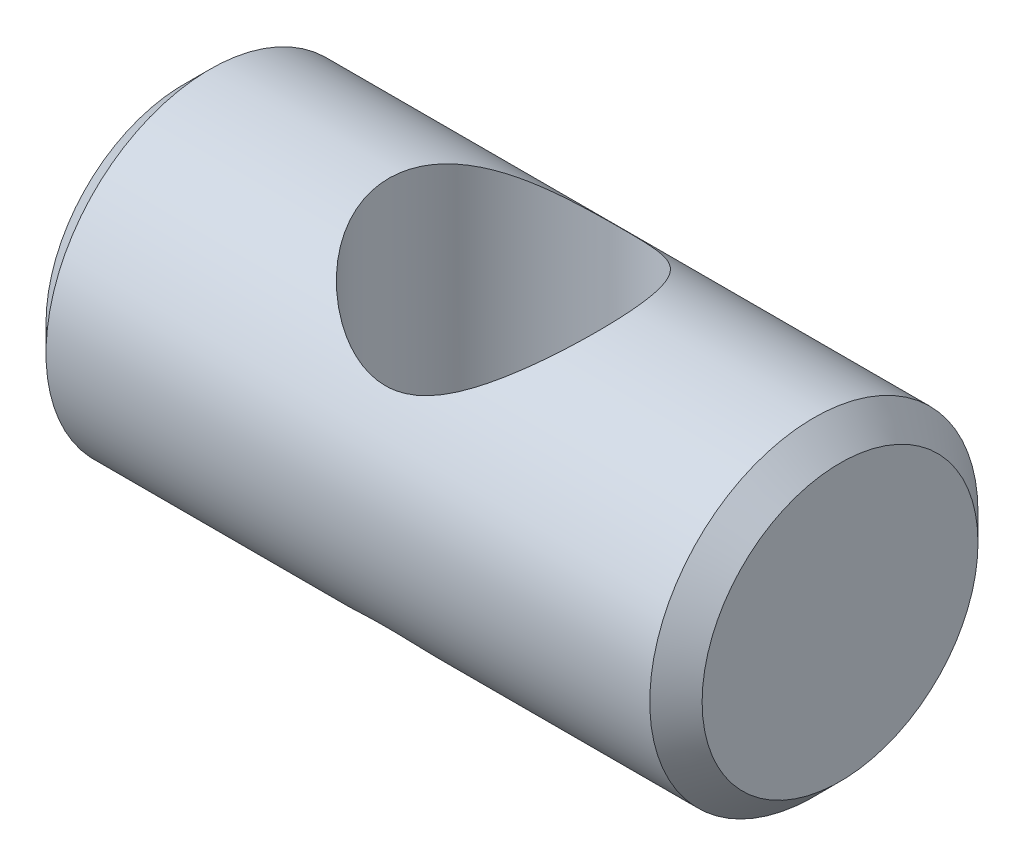
SolidWorks part; units mm, degrees
ref_plane "Front Plane" through (0, 0, 0) normal (0, 0, 1) x (1, 0, 0)
ref_plane "Top Plane" through (0, 0, 0) normal (0, 1, 0) x (1, 0, 0)
ref_plane "Right Plane" through (0, 0, 0) normal (1, 0, 0) x (0, 0, -1)
sketch "Sketch1" plane through (0, 0, 0) normal (1, 0, 0) x (0, 0, -1)
  circle A1 centre (0, 0) radius 4.765
  dimension "D1" = 9.53
extrude "Boss-Extrude1" add sketch "Sketch1" along normal mid plane 19.05
chamfer "Chamfer1" distance 0.76 angle 45 2 edges at (-9.525, 0, -4.765) (9.525, 0, -4.765)
sketch "Sketch2" plane through (0, 0, 0) normal (0, 1, 0) x (1, 0, 0)
  circle A1 centre (0, -0.25) radius 3.43
  dimension "D1" = 6.86
  dimension "D2" = 0.25
extrude "Cut-Extrude1" cut sketch "Sketch2" against normal through all both and the other way through all
